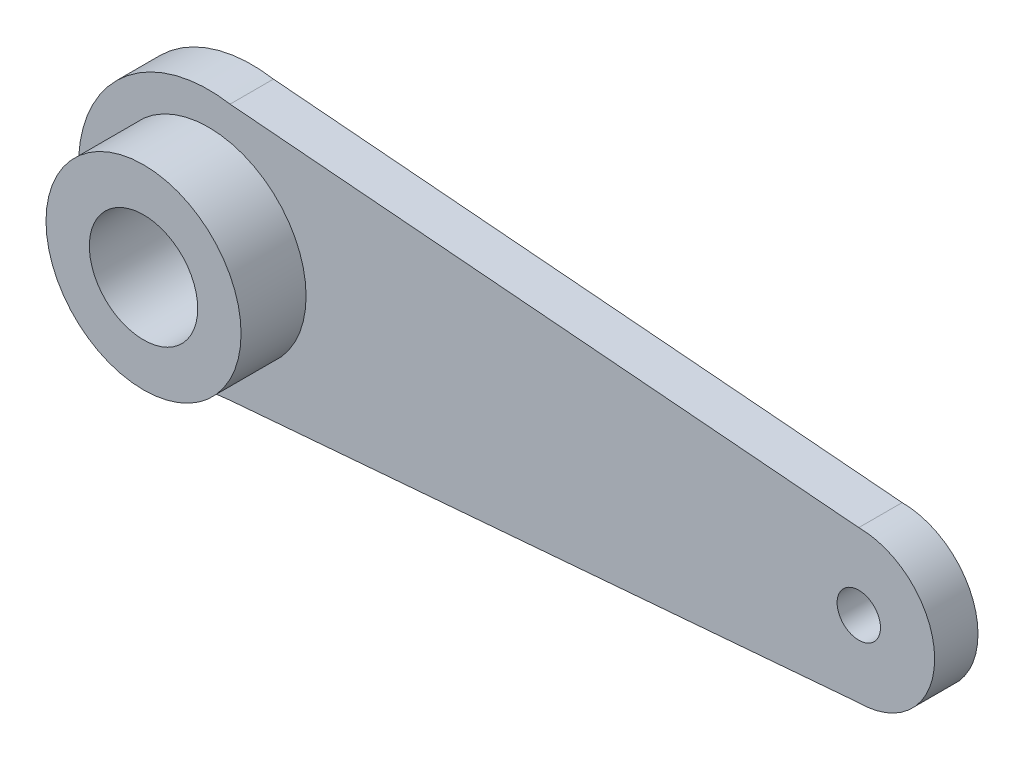
SolidWorks part; units mm, degrees
ref_plane "Front Plane" through (0, 0, 0) normal (0, 0, 1) x (1, 0, 0)
ref_plane "Top Plane" through (0, 0, 0) normal (0, 1, 0) x (1, 0, 0)
ref_plane "Right Plane" through (0, 0, 0) normal (1, 0, 0) x (0, 0, -1)
sketch "Sketch1" plane through (0, 0, 0) normal (0, 0, 1) x (1, 0, 0)
  line L0 (0, 0) -> (30, 0)
  line L1 (30, 3.5) -> (0, 6)
  line L2 (30, -3.5) -> (0, -6)
  line L3 (0, 6) -> (0, -6)
  line L4 (30, 3.5) -> (30, -3.5)
  circle A0 centre (0, 0) radius 6
  circle A1 centre (30, 0) radius 3.5
  dimension "D1" = 12
  dimension "D3" = 7
  dimension "D2" = 30
extrude "Boss-Extrude1" add sketch "Sketch1" along normal blind 2 contours A1 L1 A0 L0 | L4 A1 | L0 A1 L4 | A1 L0 A0 L2 | L4 A1 L0
sketch "Sketch2" plane through (0, 0, 2) normal (0, 0, 1) x (1, 0, 0)
  circle A0 centre (0, 0) radius 4.5
  dimension "D1" = 9
extrude "Boss-Extrude2" add sketch "Sketch2" along normal blind 3
sketch "Sketch3" plane through (0, 0, 5) normal (0, 0, 1) x (1, 0, 0)
  circle A0 centre (0, 0) radius 2.5
  dimension "D1" = 5
extrude "Cut-Extrude1" cut sketch "Sketch3" against normal through all contours A0
sketch "Sketch4" plane through (0, 0, 0) normal (0, 0, -1) x (-1, 0, 0)
  line L0 (-30, 3.5) -> (-30, -3.5)
  circle A0 centre (-30, 0) radius 1
  dimension "D1" = 2
extrude "Cut-Extrude2" cut sketch "Sketch4" against normal through all contours L0 A0 | L0 A0
